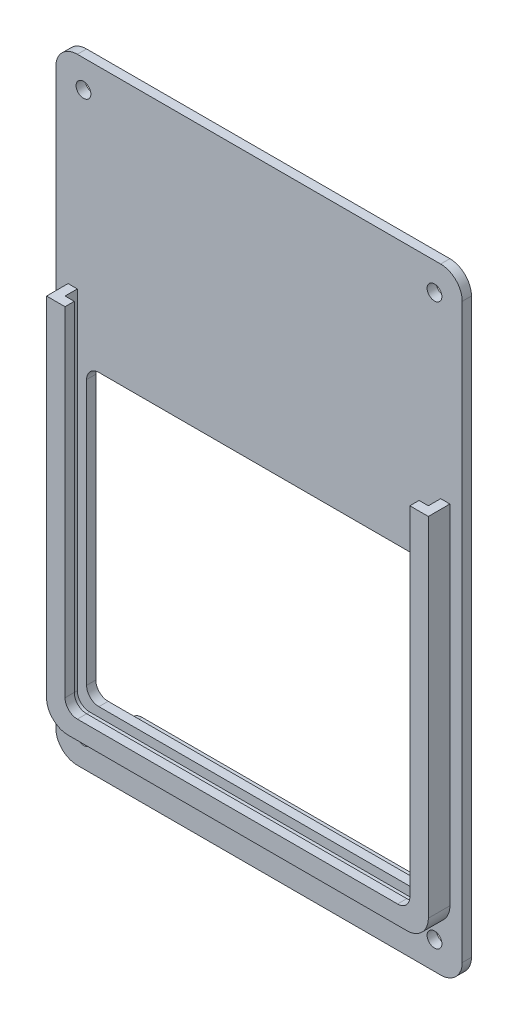
SolidWorks part; units mm, degrees
material "ABS"
ref_plane "Спереди" through (0, 0, 0) normal (0, 0, 1) x (1, 0, 0)
ref_plane "Сверху" through (0, 0, 0) normal (0, 1, 0) x (1, 0, 0)
ref_plane "Справа" through (0, 0, 0) normal (1, 0, 0) x (0, 0, -1)
sketch "Эскиз1" plane through (0, 0, 0) normal (0, 0, 1) x (1, 0, 0)
  line L1 (-33, -50) -> (33, -50)
  line L2 (-33, -50) -> (-33, 50)
  line L3 (-33, 50) -> (33, 50)
  line L4 (33, -50) -> (33, 50)
  line L5 (-33, -50) -> (33, 50) construction
  line L6 (-33, 50) -> (33, -50) construction
  point P0 (0, 0)
  dimension "D1" = 100
  dimension "D2" = 66
extrude "Бобышка-Вытянуть1" add sketch "Эскиз1" along normal blind 1.5 contours L2 L3 L4 L1
fillet "Скругление1" radius 3.5 4 edges at (-33, -50, 0.75) (33, -50, 0.75) (33, 50, 0.75) (-33, 50, 0.75)
sketch "Эскиз2" plane through (0, 0, 1.5) normal (0, 0, 1) x (1, 0, 0)
  line L0 (-29.5, -50) -> (29.5, -50) construction
  line L1 (-33, -50) -> (-24, -50)
  line L2 (-33, -50) -> (-33, -41)
  line L3 (-33, -41) -> (-24, -41)
  line L4 (-24, -50) -> (-24, -41)
  line L5 (33, -50) -> (24, -50)
  line L6 (33, -50) -> (33, -41)
  line L7 (33, -41) -> (24, -41)
  line L8 (24, -50) -> (24, -41)
  line L9 (-28, 7) -> (28, 7)
  line L10 (-28, 7) -> (-28, -40)
  line L11 (-28, -40) -> (28, -40)
  line L12 (28, 7) -> (28, -40)
  line L13 (-33, -46.5) -> (-33, 46.5) construction
  line L14 (33, -46.5) -> (33, 46.5) construction
  dimension "D1" = 57
  dimension "D2" = 5
  dimension "D3" = 5
  dimension "D4" = 10
  dimension "D5" = 9
extrude "Вырез-Вытянуть1" cut sketch "Эскиз2" against normal blind 1.5 contours L12 L9 L10 L3 L4 L11 L8 L7
fillet "Скругление2" radius 2 4 edges at (-28, -40, 0.75) (28, -40, 0.75) (-28, 7, 0.75) (28, 7, 0.75)
sketch "Эскиз3" plane through (0, 0, 1.5) normal (0, 0, 1) x (1, 0, 0)
  line L0 (-26, 7) -> (26, 7) construction
  line L1 (-28, -40) -> (28, -40)
  line L2 (-28, -40) -> (-28, 7)
  line L3 (-28, 7) -> (28, 7)
  line L4 (28, -40) -> (28, 7)
  line L5 (-29.5, -41.5) -> (29.5, -41.5)
  line L6 (-29.5, -41.5) -> (-29.5, 17)
  line L7 (-29.5, 17) -> (29.5, 17)
  line L8 (29.5, -41.5) -> (29.5, 17)
  line L10 (-26, -40) -> (26, -40) construction
  line L11 (28, 5) -> (28, -38) construction
  line L12 (-28, 5) -> (-28, -38) construction
  line L14 (-31, 17) -> (31, 17)
  line L15 (-31, 17) -> (-31, -43)
  line L16 (-31, -43) -> (31, -43)
  line L17 (31, 17) -> (31, -43)
  dimension "D1" = 1.5
  dimension "D2" = 1.5
  dimension "D3" = 1.5
  dimension "D4" = 10
  dimension "D5" = 1.5
  dimension "D6" = 1.5
  dimension "D7" = 1.5
extrude "Бобышка-Вытянуть2" add sketch "Эскиз3" along normal blind 2 contours L17 L14 L8 L5 L6 L15 L16
fillet "Скругление3" radius 2 2 edges at (29.5, -41.5, 2.5) (-29.5, -41.5, 2.5)
sketch "Эскиз4" plane through (0, 0, 3.5) normal (0, 0, 1) x (1, 0, 0)
  line L0 (-28, 5) -> (-28, -38) construction
  line L1 (-31, -43) -> (31, -43)
  line L2 (-31, -43) -> (-31, 17)
  line L3 (-31, 17) -> (31, 17)
  line L4 (31, -43) -> (31, 17)
  line L5 (-28, 17) -> (28, 17)
  line L6 (-28, 17) -> (-28, -40)
  line L7 (-28, -40) -> (28, -40)
  line L8 (28, 17) -> (28, -40)
  line L9 (-26, -40) -> (26, -40) construction
  line L10 (28, 5) -> (28, -38) construction
  line M4 (31, -43) -> (31, 17)
  line M5 (31, 17) -> (29.5, 17)
  line M6 (29.5, 17) -> (29.5, -39.5)
  arc M7 (29.5, -39.5) -> (27.5, -41.5) centre (27.5, -39.5) cw
  line M8 (27.5, -41.5) -> (-27.5, -41.5)
  arc M9 (-27.5, -41.5) -> (-29.5, -39.5) centre (-27.5, -39.5) cw
  line M10 (-29.5, -39.5) -> (-29.5, 17)
  line M11 (-29.5, 17) -> (-31, 17)
  line M12 (-31, 17) -> (-31, -43)
  line M13 (-31, -43) -> (31, -43)
extrude "Бобышка-Вытянуть3" add sketch "Эскиз4" along normal blind 1.5 contours M13 M4 M5 M6 M7 M8 M9 M10 M11 M12 | L3 L8 L7 L6 M10 M9 M8 M7 M6
fillet "Скругление4" radius 2 2 edges at (-28, -40, 4.25) (28, -40, 4.25)
fillet "Скругление5" radius 3.5 2 edges at (-31, -43, 3.25) (31, -43, 3.25)
sketch "Эскиз5" plane through (0, 0, 0) normal (0, 0, -1) x (-1, 0, 0)
  line L1 (-24, -41) -> (24, -41)
  line L2 (-24, -41) -> (-24, -48.5)
  line L3 (-24, -48.5) -> (24, -48.5)
  line L4 (24, -41) -> (24, -48.5)
  line L5 (-31.5, 48.5) -> (31.5, 48.5)
  line L6 (-31.5, 48.5) -> (-31.5, 8)
  line L7 (-31.5, 8) -> (31.5, 8)
  line L8 (31.5, 48.5) -> (31.5, 8)
  line L9 (31.5, 48.5) -> (24, 48.5)
  line L10 (31.5, 48.5) -> (31.5, 41)
  line L11 (31.5, 41) -> (24, 41)
  line L12 (24, 48.5) -> (24, 41)
  line L13 (-31.5, 48.5) -> (-24, 48.5)
  line L14 (-31.5, 48.5) -> (-31.5, 41)
  line L15 (-31.5, 41) -> (-24, 41)
  line L16 (-24, 48.5) -> (-24, 41)
  line L18 (-33, -46.5) -> (-33, 46.5) construction
  line L19 (29.5, 50) -> (-29.5, 50) construction
  line L20 (29.5, -50) -> (-29.5, -50) construction
  dimension "D1" = 7.5
  dimension "D2" = 40.5
  dimension "D3" = 63
  dimension "D4" = 1.5
  dimension "D5" = 1.5
  dimension "D6" = 7.5
  dimension "D7" = 48
  dimension "D8" = 1.5
  dimension "D9" = 9
extrude "Бобышка-Вытянуть4" add sketch "Эскиз5" along normal blind 1.5 contours L5 L16 L15 L6 L7 L8 L11 L12 | L4 L1 L2 L3
fillet "Скругление6" radius 2 12 edges at (24, 41, -0.75) (24, 48.5, -0.75) (31.5, 41, -0.75) (31.5, 8, -0.75) (-31.5, 8, -0.75) (-31.5, 41, -0.75) (-24, 41, -0.75) (-24, 48.5, -0.75) (-24, -48.5, -0.75) (-24, -41, -0.75) (24, -41, -0.75) (24, -48.5, -0.75)
sketch "Эскиз6" plane through (0, 0, 1.5) normal (0, 0, 1) x (1, 0, 0)
  line L1 (-29.5, 50) -> (29.5, 50) construction
  line L2 (-33, -46.5) -> (-33, 46.5) construction
  line L3 (33, -46.5) -> (33, 46.5) construction
  line L4 (-29.5, -50) -> (29.5, -50) construction
  point P0 (-28.5, 45.5)
  point P1 (28.5, 45.5)
  point P3 (-28.5, -45.5)
  point P4 (28.5, -45.5)
  dimension "D1" = 4.5
  dimension "D2" = 4.5
  dimension "D3" = 4.5
  dimension "D4" = 4.5
hole_wizard "Отверстие с зазором M21" positions "Эскиз7" profile "Эскиз8" hole size "M2" standard "DIN" end condition through all
sketch "Эскиз7" plane through (0, 0, 1.5) normal (0, 0, 1) x (1, 0, 0)
  point P0 (-28.5, 45.5)
  point P3 (28.5, 45.5)
  point P6 (28.5, -45.5)
  point P9 (-28.5, -45.5)
sketch "Эскиз8" plane through (-28.5, 45.5, 1.5) normal (1, 0, 0) x (0, -1, 0)
  line L0 (0, 0) -> (0, 3)
  line L1 (0, 3) -> (1.2, 3)
  line L2 (1.2, 3) -> (1.2, 0)
  line L5 (1.2, 0) -> (0, 0)
  line L11 (0, -6.35) -> (0, 107.95) construction
  dimension "Диаметр сквозного отверстия" = 2.4
  dimension "Глубина сквозного отверстия" = 3
